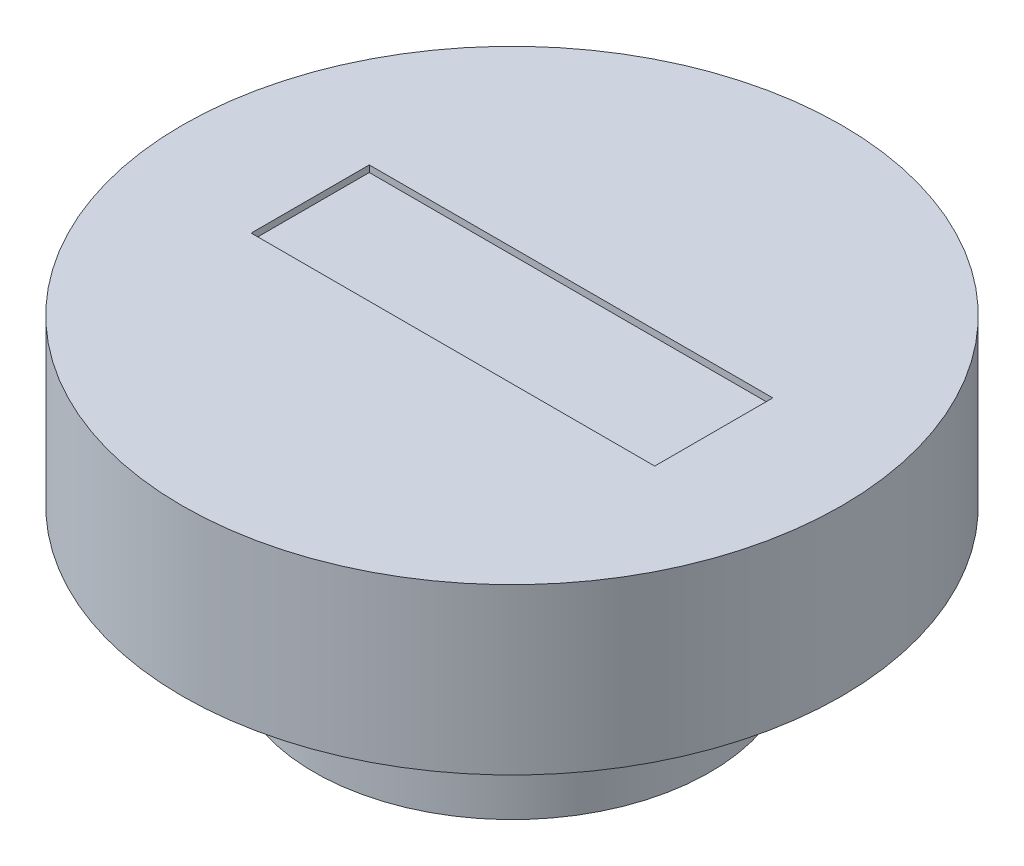
SolidWorks part; units mm, degrees
ref_plane "前视基准面" through (0, 0, 0) normal (0, 0, 1) x (1, 0, 0)
ref_plane "上视基准面" through (0, 0, 0) normal (0, 1, 0) x (1, 0, 0)
ref_plane "右视基准面" through (0, 0, 0) normal (1, 0, 0) x (0, 0, -1)
sketch "草图1" plane through (0, 0, 0) normal (0, 1, 0) x (1, 0, 0)
  circle A0 centre (0, 0) radius 10
extrude "凸台-拉伸1" add sketch "草图1" along normal blind 5
sketch "草图2" plane through (0, 0, 0) normal (0, -1, 0) x (1, 0, 0)
  circle A0 centre (0, 0) radius 6
  dimension "D1" = 12
extrude "凸台-拉伸2" add sketch "草图2" along normal blind 4
sketch "草图3" plane through (0, 5, 0) normal (0, 1, 0) x (1, 0, 0)
  line L1 (6.1197, -1.7908) -> (-6.1197, -1.7908)
  line L2 (6.1197, -1.7908) -> (6.1197, 1.7908)
  line L3 (6.1197, 1.7908) -> (-6.1197, 1.7908)
  line L4 (-6.1197, -1.7908) -> (-6.1197, 1.7908)
  line L5 (6.1197, -1.7908) -> (-6.1197, 1.7908) construction
  line L6 (6.1197, 1.7908) -> (-6.1197, -1.7908) construction
  point P0 (0, 0)
extrude "切除-拉伸1" cut sketch "草图3" against normal blind 0.2
